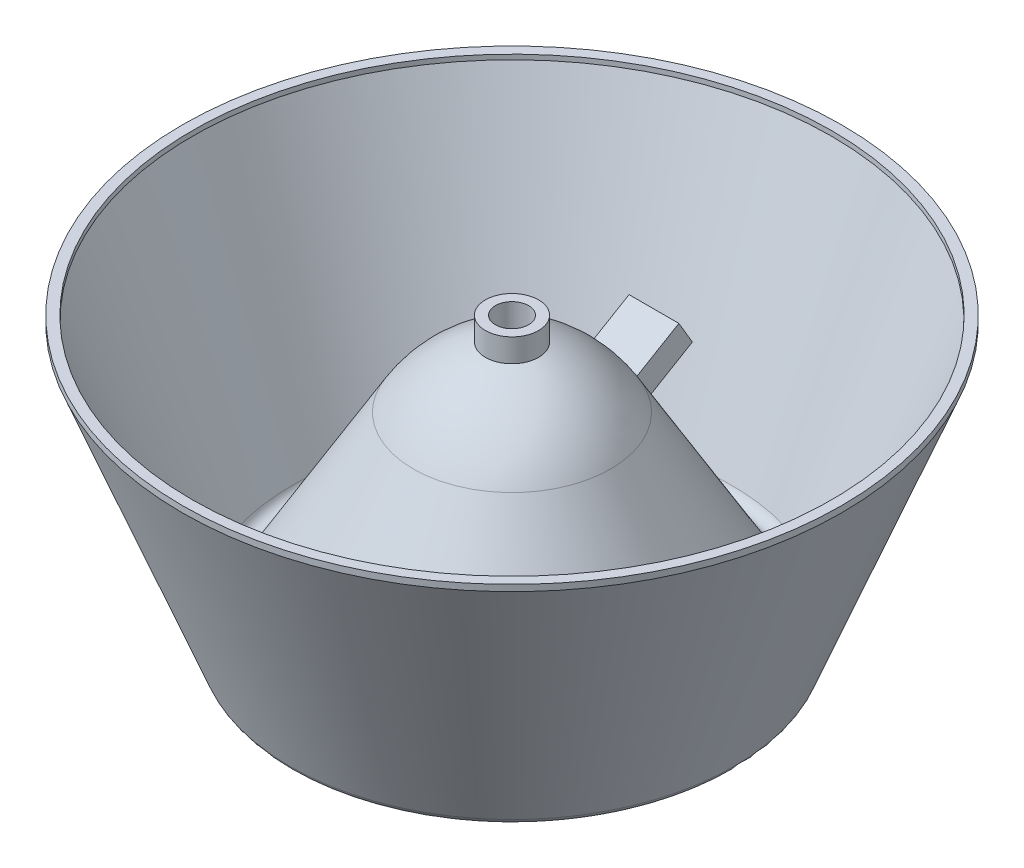
SolidWorks part; units mm, degrees
ref_plane "Front Plane" through (0, 0, 0) normal (0, 0, 1) x (1, 0, 0)
ref_plane "Top Plane" through (0, 0, 0) normal (0, 1, 0) x (1, 0, 0)
ref_plane "Right Plane" through (0, 0, 0) normal (1, 0, 0) x (0, 0, -1)
sketch "Sketch1" plane through (0, 0, 0) normal (1, 0, 0) x (0, 0, -1)
  line L5 (-100, 45) -> (100, 45) construction
  line L6 (-100, 45) -> (-100, -45) construction
  line L7 (-100, -45) -> (100, -45) construction
  line L8 (100, 45) -> (100, -45) construction
  line L9 (-100, 45) -> (100, -45) construction
  line L10 (-100, -45) -> (100, 45) construction
  line L16 (-61.3711, -39.7171) -> (-27.1309, 18.2311)
  line L19 (0, 0) -> (0, -45) construction
  line L31 (-99.2512, 43.102) -> (-66.7446, -39.292)
  line L37 (-96.2063, 43.5587) -> (-66.2059, -32.483)
  line L38 (-60.8324, -32.9081) -> (-29.7137, 19.7572)
  line L39 (-8, 37.9922) -> (-8, 45)
  line L40 (-8, 45) -> (-5, 45)
  line L41 (0, 35.8589) -> (-5, 35.8589) construction
  line L42 (-5, 35.8589) -> (-5, 45)
  line L44 (-97.2093, 46.101) -> (-63.9539, -38.191) construction
  line L45 (-63.9539, -38.191) -> (-29.7137, 19.7572) construction
  line L46 (-99.2512, 43.102) -> (-99.2512, 45)
  line L47 (-99.2512, 45) -> (-96.2512, 45)
  line L48 (-96.2512, 45) -> (-96.2063, 43.5587)
  line L49 (-100, 45) -> (-66.7446, -39.292) construction
  arc A7 (-61.3711, -39.7171) -> (-66.7446, -39.292) centre (-63.9539, -38.191) cw
  arc A9 (-29.7137, 19.7572) -> (-8, 37.9922) centre (7.0353, -1.9569) cw
  arc A10 (-27.1309, 18.2311) -> (-5, 35.8589) centre (7.0353, -1.9569) cw
  arc A11 (-60.8324, -32.9081) -> (-66.2059, -32.483) centre (-63.4152, -31.382) cw
  arc A12 (-63.9539, -38.191) -> (-63.9539, -38.191) centre (-63.9539, -38.191) cw construction
  point P0 (0, 0)
  point P14 (-7.82, -45)
  point P29 (-64.4926, -45)
  dimension "D1" = 3
  dimension "D3" = 3
  dimension "D2" = 3
revolve "Revolve7" add sketch "Sketch1" angle 360 about L19
ref_plane "Plane1" through (0, 18.1265, -30.6773) normal (0, 0.5087, -0.8609) x (-1, 0, 0)
sketch "Sketch2" plane through (0, 18.1265, -30.6773) normal (0, 0.5087, -0.8609) x (-1, 0, 0)
  line L0 (0, 0) -> (0, -58.519) construction
  line L1 (-7.5, 0) -> (7.5, 0)
  line L2 (7.5, 0) -> (7.5, -50)
  line L4 (-7.5, 0) -> (-7.5, -50)
  line L5 (-7.5, -50) -> (7.5, -50)
  point P6 (0, 0)
extrude "Cut-Extrude1" cut sketch "Sketch2" against normal blind 1
ref_plane "Plane2" through (0, 17.6178, -29.8164) normal (0, 0.5087, -0.8609) x (-1, 0, 0)
sketch "Sketch5" plane through (0, 17.6178, -29.8164) normal (0, 0.5087, -0.8609) x (-1, 0, 0)
  line L0 (-7.5, 0) -> (-7.5, -50) construction
  line L1 (7.5, 0) -> (-7.5, 0)
  line L2 (7.5, 0) -> (7.5, -8)
  line L3 (7.5, -8) -> (-7.5, -8)
  line L4 (-7.5, 0) -> (-7.5, -8)
extrude "Boss-Extrude1" add sketch "Sketch5" along normal blind 15
